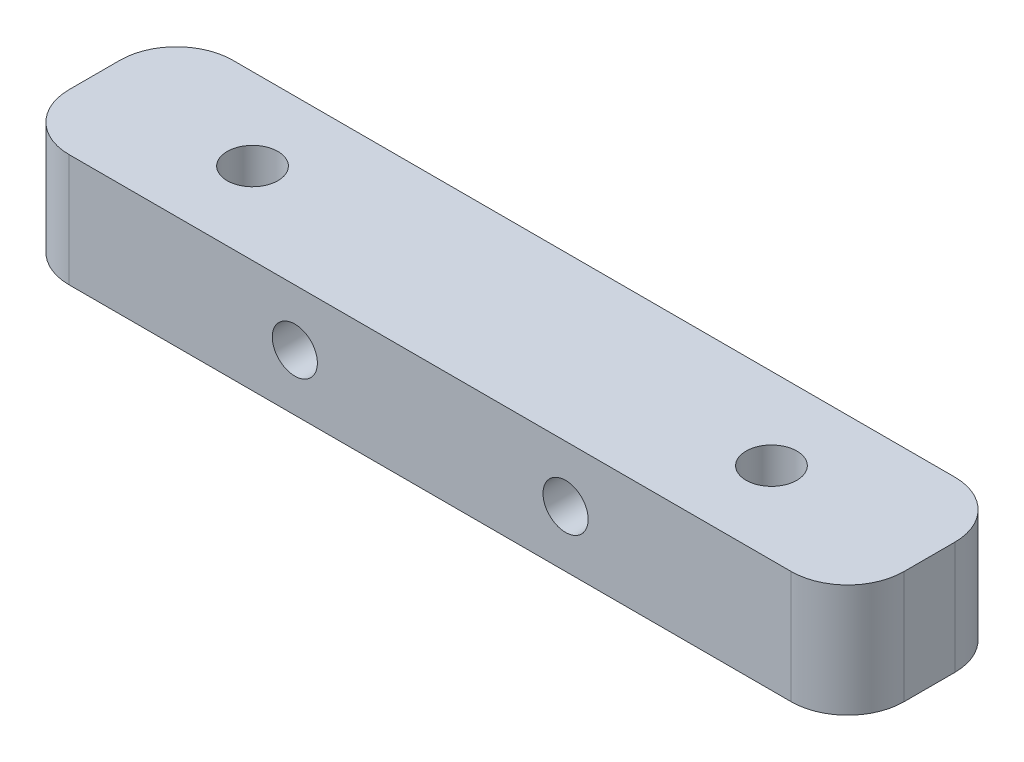
SolidWorks part; units mm, degrees
ref_plane "Front Plane" through (0, 0, 0) normal (0, 0, 1) x (1, 0, 0)
ref_plane "Top Plane" through (0, 0, 0) normal (0, 1, 0) x (1, 0, 0)
ref_plane "Right Plane" through (0, 0, 0) normal (1, 0, 0) x (0, 0, -1)
sketch "Sketch1" plane through (0, 0, 0) normal (0, 1, 0) x (1, 0, 0)
  line L0 (32, 7.25) -> (-32, 7.25)
  line L1 (-37, 2.25) -> (-37, -7.25)
  line L2 (-37, -7.25) -> (37, -7.25)
  line L3 (37, -7.25) -> (37, 2.25)
  circle A0 centre (23, 0) radius 2.25
  circle A1 centre (-23, 0) radius 2.25
  arc A2 (37, 2.25) -> (32, 7.25) centre (32, 2.25) ccw
  arc A3 (-32, 7.25) -> (-37, 2.25) centre (-32, 2.25) ccw
  dimension "D1" = 7.25
extrude "Boss-Extrude1" add sketch "Sketch1" along normal blind 10
fillet "Fillet1" radius 5 2 edges at (37, 5, 7.25) (-37, 5, 7.25)
sketch "Sketch2" plane through (0, 0, -7.25) normal (0, 0, -1) x (-1, 0, 0)
  line L0 (-32, 5) -> (32, 5) construction
  line L1 (-32, 10) -> (-32, 0) construction
  line L2 (32, 10) -> (32, 0) construction
  circle A0 centre (-12, 5) radius 2
  circle A1 centre (12, 5) radius 2
  dimension "D1" = 20
  dimension "D2" = 20
  dimension "D3" = 4
  dimension "D4" = 4
extrude "Cut-Extrude1" cut sketch "Sketch2" against normal blind 24
